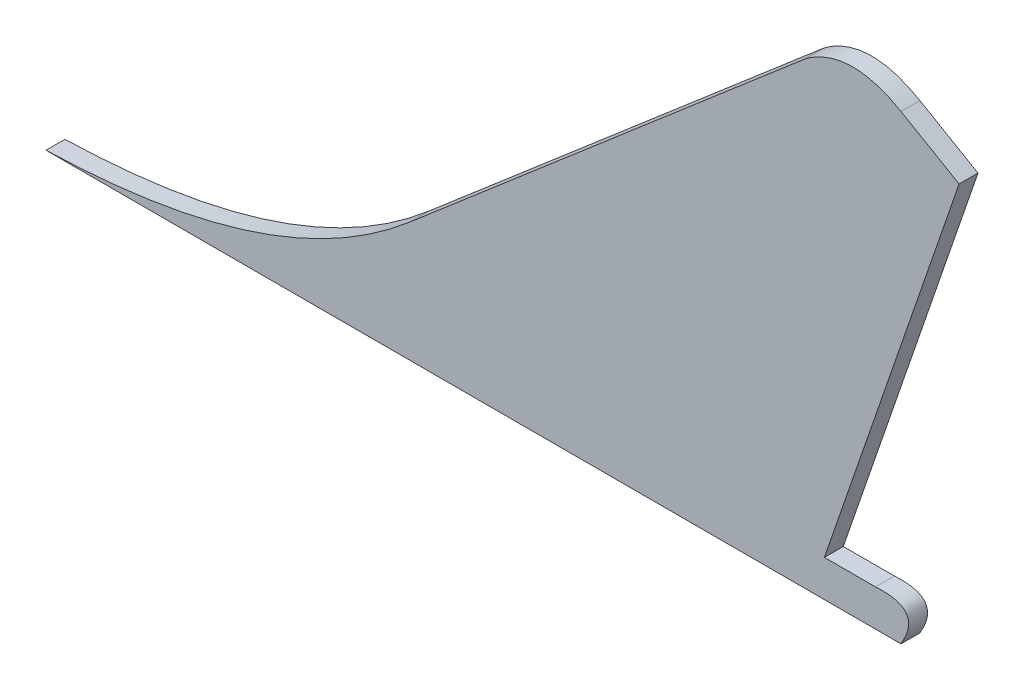
SolidWorks part; units mm, degrees
ref_plane "Plan de face" through (0, 0, 0) normal (0, 0, 1) x (1, 0, 0)
ref_plane "Plan de dessus" through (0, 0, 0) normal (0, 1, 0) x (1, 0, 0)
ref_plane "Plan de droite" through (0, 0, 0) normal (1, 0, 0) x (0, 0, -1)
sketch "Esquisse1" plane through (0, 0, 0) normal (0, 0, 1) x (1, 0, 0)
  line L0 (134.6667, 149) -> (673.3333, 149) construction
  line L1 (11654.9305, 3598.5296) -> (13748.2847, 5393.368)
  line L2 (14253.577, 5404.4815) -> (14561.065, 5225.9023)
  line L3 (14561.065, 5225.9023) -> (13848.2454, 3158.6032)
  line L4 (13848.2454, 3158.6032) -> (14118.8324, 3158.6032)
  line L5 (9730.0072, 2965.0573) -> (14253.577, 2965.0573)
  spline S0 degree 3 poles (9730.0072, 2965.0573) (10415.4411, 2985.3081) (11109.5753, 3130.943) (11654.9305, 3598.5296) knots 0 0 0 0 1 1 1 1
  spline S1 degree 3 poles (13748.2847, 5393.368) (13902.8888, 5506.6263) (14071.3196, 5510.3308) (14253.577, 5404.4815) knots 0 0 0 0 1 1 1 1
  spline S2 degree 2 poles (14118.8324, 3158.6032) (14378.396, 3174.2113) (14253.577, 2965.0573) knots 0 0 0 1 1 1
extrude "Boss.-Extru.1" add sketch "Esquisse1" along normal blind 100
